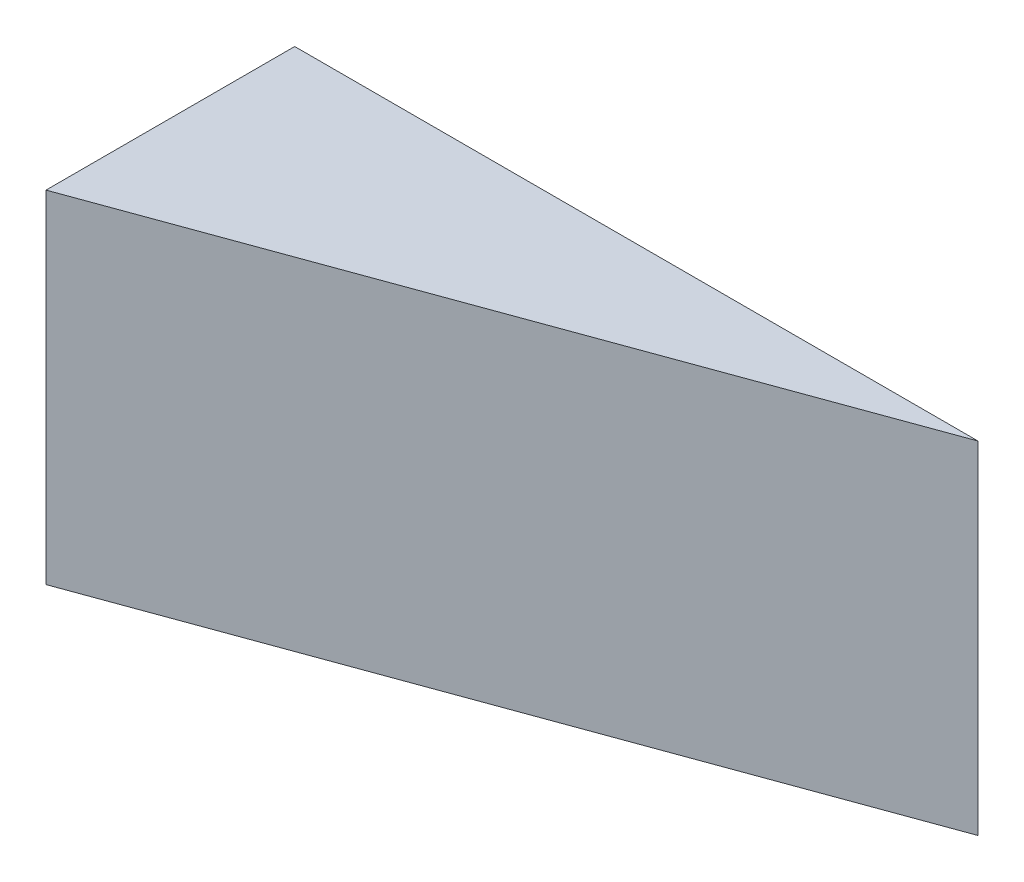
SolidWorks part; units mm, degrees
ref_plane "Přední rovina" through (0, 0, 0) normal (0, 0, 1) x (1, 0, 0)
ref_plane "Horní rovina" through (0, 0, 0) normal (0, 1, 0) x (1, 0, 0)
ref_plane "Pravá rovina" through (0, 0, 0) normal (1, 0, 0) x (0, 0, -1)
sketch "Sketch1" plane through (0, 0, 0) normal (0, 1, 0) x (1, 0, 0)
  line L0 (0, 0) -> (40, 0)
  line L1 (40, 0) -> (0, -14.5588)
  line L2 (0, -14.5588) -> (0, 0)
  point P4 (0, 0)
  point P5 (0, 0)
  dimension "D1" = 20
  dimension "D2" = 40
extrude "Boss-Extrude1" add sketch "Sketch1" along normal blind 20
